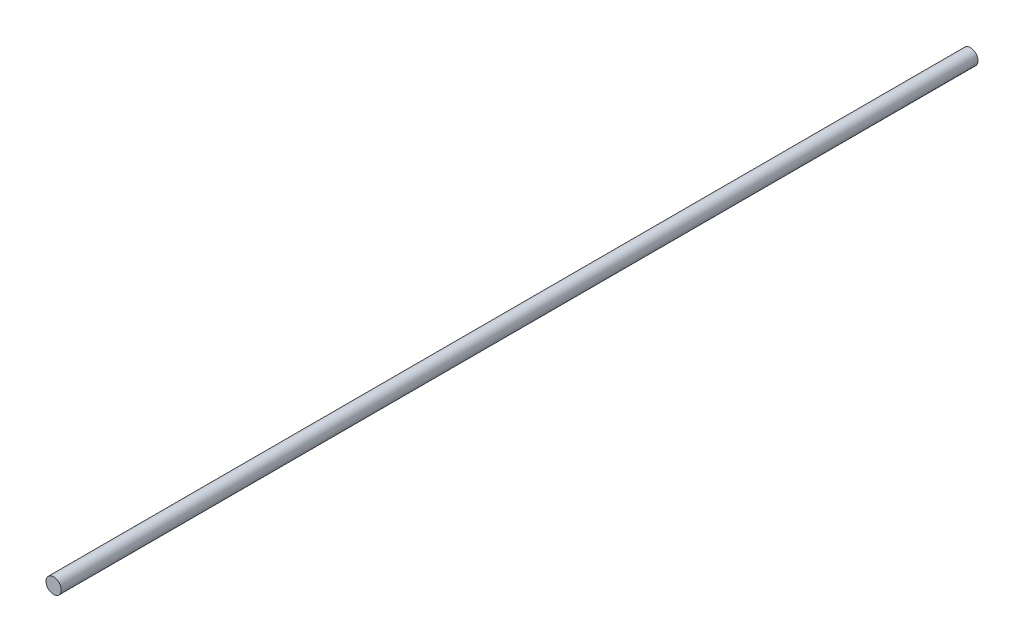
SolidWorks part; units mm, degrees
material "1.4000 (X6Cr13)"
ref_plane "Ebene vorne" through (0, 0, 0) normal (0, 0, 1) x (1, 0, 0)
ref_plane "Ebene oben" through (0, 0, 0) normal (0, 1, 0) x (1, 0, 0)
ref_plane "Ebene rechts" through (0, 0, 0) normal (1, 0, 0) x (0, 0, -1)
sketch "Skizze1" plane through (0, 0, 0) normal (0, 0, 1) x (1, 0, 0)
  circle A0 centre (0, 0) radius 4
extrude "Aufsatz-Linear austragen1" add sketch "Skizze1" along normal blind 480
